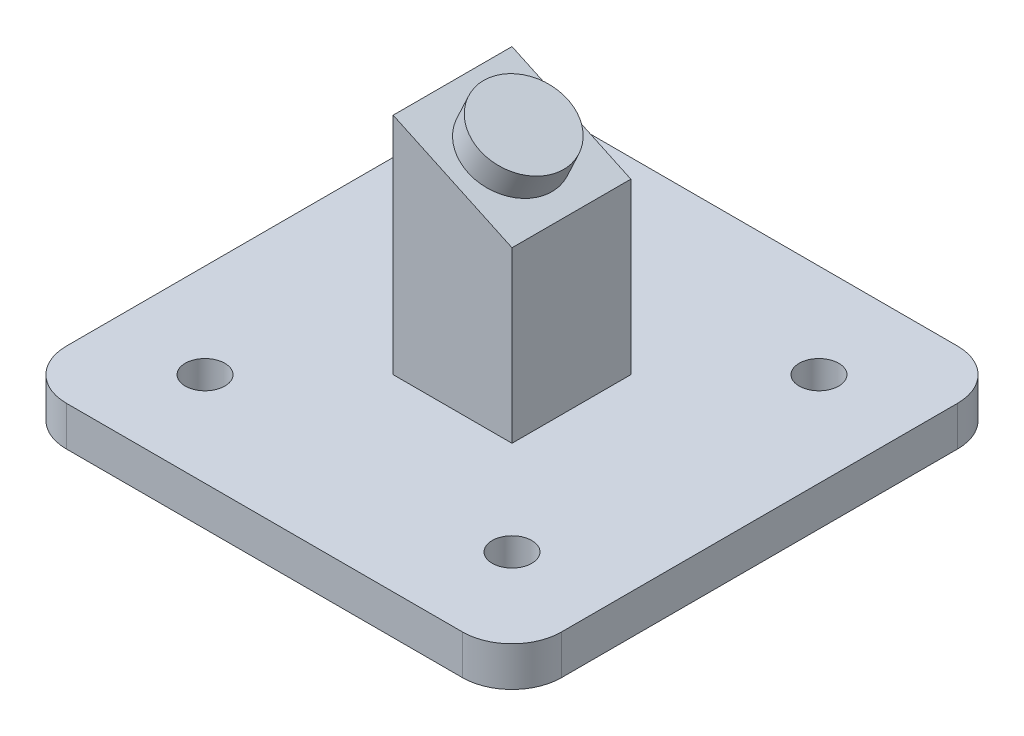
SolidWorks part; units mm, degrees
ref_plane "Front Plane" through (0, 0, 0) normal (0, 0, 1) x (1, 0, 0)
ref_plane "Top Plane" through (0, 0, 0) normal (0, 1, 0) x (1, 0, 0)
ref_plane "Right Plane" through (0, 0, 0) normal (1, 0, 0) x (0, 0, -1)
sketch "Sketch1" plane through (0, 0, 0) normal (0, 1, 0) x (1, 0, 0)
  line L0 (25, 31) -> (25, 19) construction
  line L1 (5, 0) -> (45, 0)
  line L2 (0, 5) -> (0, 45)
  line L3 (5, 50) -> (45, 50)
  line L4 (50, 5) -> (50, 45)
  line L5 (19, 19) -> (31, 19) construction
  line L6 (19, 19) -> (19, 31) construction
  line L7 (19, 31) -> (31, 31) construction
  line L8 (31, 19) -> (31, 31) construction
  line L9 (19, 25) -> (31, 25) construction
  line L10 (9.5, 9.5) -> (9.5, 40.5) construction
  line L11 (9.5, 40.5) -> (40.5, 40.5) construction
  line L12 (40.5, 40.5) -> (40.5, 9.5) construction
  line L13 (40.5, 9.5) -> (9.5, 9.5) construction
  arc A0 (45, 50) -> (50, 45) centre (45, 45) cw
  arc A1 (45, 0) -> (50, 5) centre (45, 5) ccw
  arc A2 (5, 0) -> (0, 5) centre (5, 5) cw
  arc A3 (0, 45) -> (5, 50) centre (5, 45) cw
  circle A4 centre (9.5, 9.5) radius 2
  circle A5 centre (9.5, 40.5) radius 2
  circle A6 centre (40.5, 40.5) radius 2
  circle A7 centre (40.5, 9.5) radius 2
  point P11 (0, 0)
  point P14 (0, 50)
  dimension "D2" = 5
  dimension "D4" = 4
  dimension "D1" = 50
  dimension "D3" = 12
extrude "Boss-Extrude1" add sketch "Sketch1" along normal blind 4
sketch "Sketch3" plane through (0, 4, 0) normal (0, 1, 0) x (1, 0, 0)
  line L1 (19, 31) -> (31, 31)
  line L2 (19, 31) -> (19, 19)
  line L3 (19, 19) -> (31, 19)
  line L4 (31, 31) -> (31, 19)
extrude "Boss-Extrude3" add sketch "Sketch3" along normal blind 17.1
sketch "Sketch5" plane through (0, 0, -19) normal (0, 0, 1) x (1, 0, 0)
  line L0 (31, 21.1) -> (19, 26.6957)
  line L1 (19, 26.6957) -> (19, 21.1)
  line L2 (19, 21.1) -> (31, 21.1)
  dimension "D1" = 25
extrude "Boss-Extrude4" add sketch "Sketch5" against normal up to surface (12 mm away) up to face at (25, 12.55, -31)
sketch "Sketch6" plane through (13.6186, 29.2051, 0) normal (0.4226, 0.9063, 0) x (0.9063, -0.4226, 0)
  line L0 (12.558, 25) -> (5.9378, 25) construction
  line L1 (5.9378, 31) -> (5.9378, 19) construction
  line L2 (12.558, 25) -> (12.558, 31) construction
  line L3 (5.9378, 31) -> (19.1783, 31) construction
  circle A0 centre (12.558, 25) radius 4.45
  dimension "D1" = 8.9
extrude "Boss-Extrude5" add sketch "Sketch6" along normal blind 2.8
